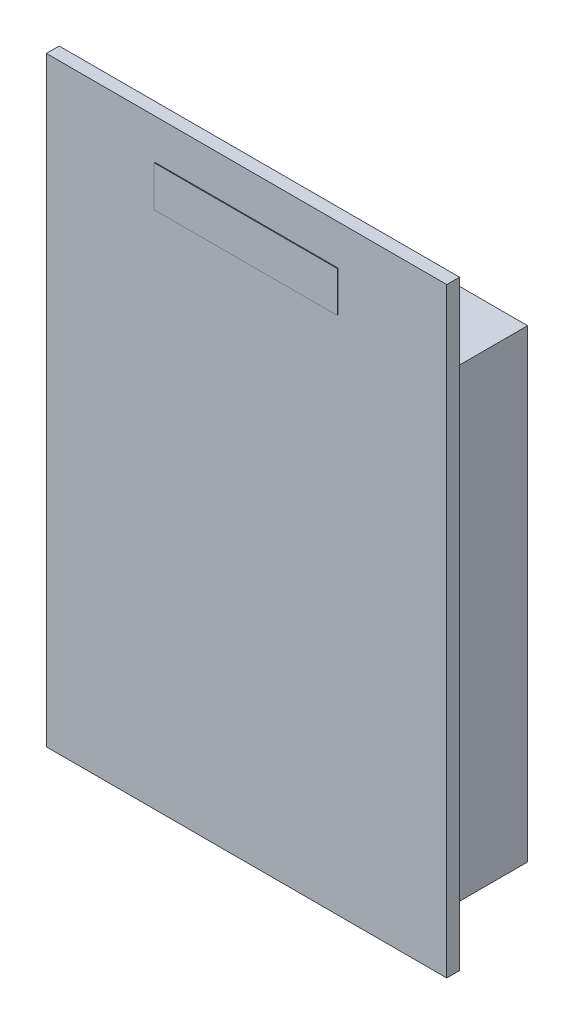
SolidWorks part; units mm, degrees
ref_plane "Front Plane" through (0, 0, 0) normal (0, 0, 1) x (1, 0, 0)
ref_plane "Top Plane" through (0, 0, 0) normal (0, 1, 0) x (1, 0, 0)
ref_plane "Right Plane" through (0, 0, 0) normal (1, 0, 0) x (0, 0, -1)
sketch "Sketch1" plane through (0, 0, 0) normal (0, 0, 1) x (1, 0, 0)
  line L1 (25, -37.5) -> (-25, -37.5)
  line L2 (25, -37.5) -> (25, 37.5)
  line L3 (25, 37.5) -> (-25, 37.5)
  line L4 (-25, -37.5) -> (-25, 37.5)
  line L5 (25, -37.5) -> (-25, 37.5) construction
  line L6 (25, 37.5) -> (-25, -37.5) construction
  point P0 (0, 0)
  dimension "D1" = 50
  dimension "D2" = 75
extrude "Boss-Extrude1" add sketch "Sketch1" along normal blind 1.6
sketch "Sketch5" plane through (0, 0, 0) normal (0, 0, 1) x (1, 0, 0)
  line L0 (-25.3238, 38.0215) -> (25.4762, 38.0215) construction
  dimension "D1" = 50.8
sketch "Sketch3" plane through (0, 0, 1.6) normal (0, 0, 1) x (1, 0, 0)
  line L0 (25, 37.5) -> (-25, 37.5) construction
  line L1 (-11.43, 27.42) -> (11.43, 27.42)
  line L2 (-11.43, 27.42) -> (-11.43, 32.5)
  line L3 (-11.43, 32.5) -> (11.43, 32.5)
  line L4 (11.43, 27.42) -> (11.43, 32.5)
  line L5 (-11.43, 27.42) -> (11.43, 32.5) construction
  line L6 (-11.43, 32.5) -> (11.43, 27.42) construction
  point P0 (0, 29.96)
  dimension "D1" = 22.86
  dimension "D2" = 5.08
  dimension "D3" = 5
extrude "Boss-Extrude2" add sketch "Sketch3" along normal blind 0.1
sketch "Sketch6" plane through (0, 0, 0) normal (0, 0, -1) x (-1, 0, 0)
  line L0 (25, -37.5) -> (-25, -37.5) construction
  line L1 (17.5, -37.5) -> (-17.5, -37.5)
  line L2 (17.5, -37.5) -> (17.5, 20.5)
  line L3 (17.5, 20.5) -> (-17.5, 20.5)
  line L4 (-17.5, -37.5) -> (-17.5, 20.5)
  line L5 (17.5, -37.5) -> (-17.5, 20.5) construction
  line L6 (17.5, 20.5) -> (-17.5, -37.5) construction
  point P0 (0, -8.5)
  point P5 (-16.0238, -38.1)
  point P8 (0, 0)
  dimension "D1" = 58
  dimension "D2" = 35
extrude "Boss-Extrude3" add sketch "Sketch6" along normal blind 16
